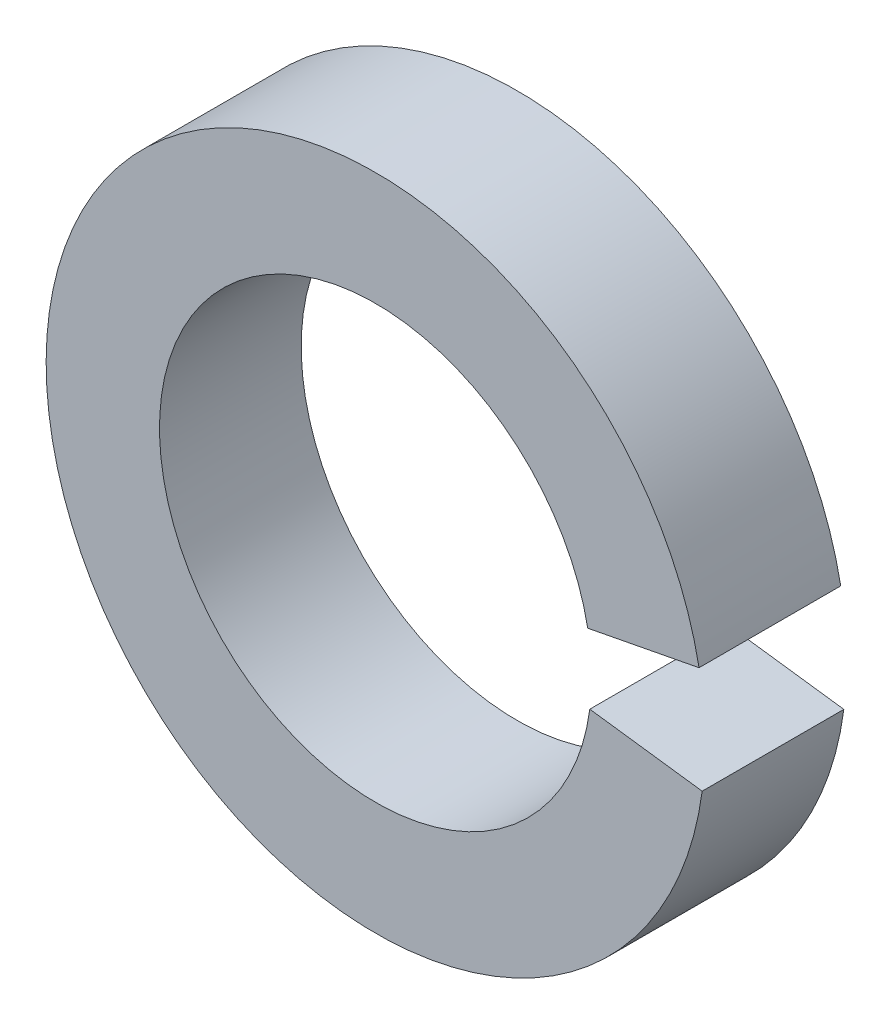
SolidWorks part; units mm, degrees
ref_plane "前视基准面" through (0, 0, 0) normal (0, 0, 1) x (1, 0, 0)
ref_plane "上视基准面" through (0, 0, 0) normal (0, 1, 0) x (1, 0, 0)
ref_plane "右视基准面" through (0, 0, 0) normal (1, 0, 0) x (0, 0, -1)
sketch "草图1" plane through (0, 0, 0) normal (0, 0, 1) x (1, 0, 0)
  line L0 (2.995, 0.5767) -> (4.5661, 0.8792)
  line L1 (3.0238, -0.3986) -> (4.6101, -0.6077)
  arc A0 (2.995, 0.5767) -> (3.0238, -0.3986) centre (0, 0) ccw
  arc A1 (4.5661, 0.8792) -> (4.6101, -0.6077) centre (0, 0) ccw
extrude "凸台-拉伸1" add sketch "草图1" along normal blind 2
